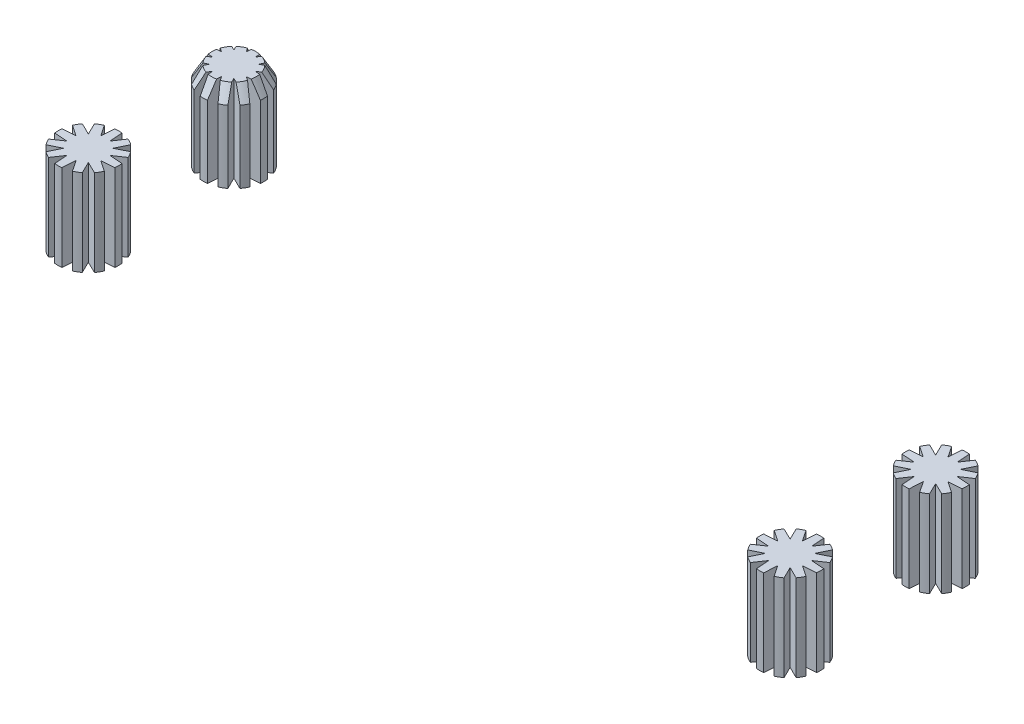
SolidWorks part; units mm, degrees
ref_plane "Front Plane" through (0, 0, 0) normal (0, 0, 1) x (1, 0, 0)
ref_plane "Top Plane" through (0, 0, 0) normal (0, 1, 0) x (1, 0, 0)
ref_plane "Right Plane" through (0, 0, 0) normal (1, 0, 0) x (0, 0, -1)
sketch "Sketch2" plane through (0, 0, 0) normal (0, 1, 0) x (1, 0, 0)
  line L0 (-22.25, 13.4082) -> (-22.25, -6080.7708) construction
  line L1 (-20.25, -10) -> (20.25, -10) construction
  line L2 (-20.25, -10) -> (-20.25, 10) construction
  line L3 (-20.25, 10) -> (20.25, 10) construction
  line L4 (20.25, -10) -> (20.25, 10) construction
  line L5 (-20.25, -10) -> (20.25, 10) construction
  line L6 (-20.25, 10) -> (20.25, -10) construction
  line L7 (0, 0) -> (-50000, 0) construction
  line L9 (0, 0) -> (0, 50000) construction
  point P0 (0, 0)
  dimension "D1" = 2
  dimension "D3" = 40.5
  dimension "D4" = 20
sketch "Sketch4" plane through (0, 0, 0) normal (0, 1, 0) x (1, 0, 0)
  line L0 (-24.35, 5.0484) -> (-24.35, 50005.0484) construction
  line L1 (-24.6, 7.1351) -> (-24.6798, 5.9941)
  line L2 (-24.1, 7.1351) -> (-24.0202, 5.9941)
  line L3 (-22.25, 200013.4082) -> (-22.25, -206080.7708) construction
  line L4 (200000, 0) -> (-250000, 0) construction
  line L5 (-23.091, 6.7307) -> (-23.5924, 5.7027)
  line L6 (-23.524, 6.9807) -> (-24.1636, 6.0325)
  line L7 (-22.4193, 5.876) -> (-23.3675, 5.2364)
  line L8 (-22.6693, 6.309) -> (-23.6973, 5.8076)
  line L9 (-22.2649, 4.8) -> (-23.4059, 4.7202)
  line L10 (-22.2649, 5.3) -> (-23.4059, 5.3798)
  line L11 (-22.6693, 3.791) -> (-23.6973, 4.2924)
  line L12 (-22.4193, 4.224) -> (-23.3675, 4.8636)
  line L13 (-23.524, 3.1193) -> (-24.1636, 4.0675)
  line L14 (-23.091, 3.3693) -> (-23.5924, 4.3973)
  line L15 (-24.6, 2.9649) -> (-24.6798, 4.1059)
  line L16 (-24.1, 2.9649) -> (-24.0202, 4.1059)
  line L17 (-25.609, 3.3693) -> (-25.1076, 4.3973)
  line L18 (-25.176, 3.1193) -> (-24.5364, 4.0675)
  line L19 (-26.2807, 4.224) -> (-25.3325, 4.8636)
  line L20 (-26.0307, 3.791) -> (-25.0027, 4.2924)
  line L21 (-26.4351, 5.3) -> (-25.2941, 5.3798)
  line L22 (-26.4351, 4.8) -> (-25.2941, 4.7202)
  line L23 (-26.0307, 6.309) -> (-25.0027, 5.8076)
  line L24 (-26.2807, 5.876) -> (-25.3325, 5.2364)
  line L25 (-25.176, 6.9807) -> (-24.5364, 6.0325)
  line L26 (-25.609, 6.7307) -> (-25.1076, 5.7027)
  line L27 (0, 0) -> (-50000, 0) construction
  line L28 (0, 0) -> (0, 50000) construction
  line L29 (-25.609, -6.7307) -> (-25.1076, -5.7027)
  line L30 (-25.176, -6.9807) -> (-24.5364, -6.0325)
  line L31 (-26.2807, -5.876) -> (-25.3325, -5.2364)
  line L32 (-26.0307, -6.309) -> (-25.0027, -5.8076)
  line L33 (-26.4351, -4.8) -> (-25.2941, -4.7202)
  line L34 (-26.4351, -5.3) -> (-25.2941, -5.3798)
  line L35 (-26.0307, -3.791) -> (-25.0027, -4.2924)
  line L36 (-26.2807, -4.224) -> (-25.3325, -4.8636)
  line L37 (-25.176, -3.1193) -> (-24.5364, -4.0675)
  line L38 (-25.609, -3.3693) -> (-25.1076, -4.3973)
  line L39 (-24.1, -2.9649) -> (-24.0202, -4.1059)
  line L40 (-24.6, -2.9649) -> (-24.6798, -4.1059)
  line L41 (-23.091, -3.3693) -> (-23.5924, -4.3973)
  line L42 (-23.524, -3.1193) -> (-24.1636, -4.0675)
  line L43 (-22.4193, -4.224) -> (-23.3675, -4.8636)
  line L44 (-22.6693, -3.791) -> (-23.6973, -4.2924)
  line L45 (-22.2649, -5.3) -> (-23.4059, -5.3798)
  line L46 (-22.2649, -4.8) -> (-23.4059, -4.7202)
  line L47 (-22.6693, -6.309) -> (-23.6973, -5.8076)
  line L48 (-22.4193, -5.876) -> (-23.3675, -5.2364)
  line L49 (-23.524, -6.9807) -> (-24.1636, -6.0325)
  line L50 (-23.091, -6.7307) -> (-23.5924, -5.7027)
  line L51 (-24.1, -7.1351) -> (-24.0202, -5.9941)
  line L52 (-24.6, -7.1351) -> (-24.6798, -5.9941)
  line L53 (24.6, -7.1351) -> (24.6798, -5.9941)
  line L54 (24.1, -7.1351) -> (24.0202, -5.9941)
  line L55 (23.091, -6.7307) -> (23.5924, -5.7027)
  line L56 (23.524, -6.9807) -> (24.1636, -6.0325)
  line L57 (22.4193, -5.876) -> (23.3675, -5.2364)
  line L58 (22.6693, -6.309) -> (23.6973, -5.8076)
  line L59 (22.2649, -4.8) -> (23.4059, -4.7202)
  line L60 (22.2649, -5.3) -> (23.4059, -5.3798)
  line L61 (22.6693, -3.791) -> (23.6973, -4.2924)
  line L62 (22.4193, -4.224) -> (23.3675, -4.8636)
  line L63 (23.524, -3.1193) -> (24.1636, -4.0675)
  line L64 (23.091, -3.3693) -> (23.5924, -4.3973)
  line L65 (24.6, -2.9649) -> (24.6798, -4.1059)
  line L66 (24.1, -2.9649) -> (24.0202, -4.1059)
  line L67 (25.609, -3.3693) -> (25.1076, -4.3973)
  line L68 (25.176, -3.1193) -> (24.5364, -4.0675)
  line L69 (26.2807, -4.224) -> (25.3325, -4.8636)
  line L70 (26.0307, -3.791) -> (25.0027, -4.2924)
  line L71 (26.4351, -5.3) -> (25.2941, -5.3798)
  line L72 (26.4351, -4.8) -> (25.2941, -4.7202)
  line L73 (26.0307, -6.309) -> (25.0027, -5.8076)
  line L74 (26.2807, -5.876) -> (25.3325, -5.2364)
  line L75 (25.176, -6.9807) -> (24.5364, -6.0325)
  line L76 (25.609, -6.7307) -> (25.1076, -5.7027)
  line L77 (25.609, 6.7307) -> (25.1076, 5.7027)
  line L78 (25.176, 6.9807) -> (24.5364, 6.0325)
  line L79 (26.2807, 5.876) -> (25.3325, 5.2364)
  line L80 (26.0307, 6.309) -> (25.0027, 5.8076)
  line L81 (26.4351, 4.8) -> (25.2941, 4.7202)
  line L82 (26.4351, 5.3) -> (25.2941, 5.3798)
  line L83 (26.0307, 3.791) -> (25.0027, 4.2924)
  line L84 (26.2807, 4.224) -> (25.3325, 4.8636)
  line L85 (25.176, 3.1193) -> (24.5364, 4.0675)
  line L86 (25.609, 3.3693) -> (25.1076, 4.3973)
  line L87 (24.1, 2.9649) -> (24.0202, 4.1059)
  line L88 (24.6, 2.9649) -> (24.6798, 4.1059)
  line L89 (23.091, 3.3693) -> (23.5924, 4.3973)
  line L90 (23.524, 3.1193) -> (24.1636, 4.0675)
  line L91 (22.4193, 4.224) -> (23.3675, 4.8636)
  line L92 (22.6693, 3.791) -> (23.6973, 4.2924)
  line L93 (22.2649, 5.3) -> (23.4059, 5.3798)
  line L94 (22.2649, 4.8) -> (23.4059, 4.7202)
  line L95 (22.6693, 6.309) -> (23.6973, 5.8076)
  line L96 (22.4193, 5.876) -> (23.3675, 5.2364)
  line L97 (23.524, 6.9807) -> (24.1636, 6.0325)
  line L98 (23.091, 6.7307) -> (23.5924, 5.7027)
  line L99 (24.1, 7.1351) -> (24.0202, 5.9941)
  line L100 (24.6, 7.1351) -> (24.6798, 5.9941)
  circle A0 centre (-24.35, 5.05) radius 1 construction
  circle A2 centre (-24.35, 5.05) radius 2.1 construction
  arc A3 (-24.1, 7.1351) -> (-24.6, 7.1351) centre (-24.35, 5.05) ccw
  arc A4 (-24.6798, 5.9941) -> (-24.0202, 5.9941) centre (-24.35, 5.05) cw
  arc A5 (-23.091, 6.7307) -> (-23.524, 6.9807) centre (-24.35, 5.05) ccw
  arc A6 (-24.1636, 6.0325) -> (-23.5924, 5.7027) centre (-24.35, 5.05) cw
  arc A7 (-22.4193, 5.876) -> (-22.6693, 6.309) centre (-24.35, 5.05) ccw
  arc A8 (-23.6973, 5.8076) -> (-23.3675, 5.2364) centre (-24.35, 5.05) cw
  arc A9 (-22.2649, 4.8) -> (-22.2649, 5.3) centre (-24.35, 5.05) ccw
  arc A10 (-23.4059, 5.3798) -> (-23.4059, 4.7202) centre (-24.35, 5.05) cw
  arc A11 (-22.6693, 3.791) -> (-22.4193, 4.224) centre (-24.35, 5.05) ccw
  arc A12 (-23.3675, 4.8636) -> (-23.6973, 4.2924) centre (-24.35, 5.05) cw
  arc A13 (-23.524, 3.1193) -> (-23.091, 3.3693) centre (-24.35, 5.05) ccw
  arc A14 (-23.5924, 4.3973) -> (-24.1636, 4.0675) centre (-24.35, 5.05) cw
  arc A15 (-24.6, 2.9649) -> (-24.1, 2.9649) centre (-24.35, 5.05) ccw
  arc A16 (-24.0202, 4.1059) -> (-24.6798, 4.1059) centre (-24.35, 5.05) cw
  arc A17 (-25.609, 3.3693) -> (-25.176, 3.1193) centre (-24.35, 5.05) ccw
  arc A18 (-24.5364, 4.0675) -> (-25.1076, 4.3973) centre (-24.35, 5.05) cw
  arc A19 (-26.2807, 4.224) -> (-26.0307, 3.791) centre (-24.35, 5.05) ccw
  arc A20 (-25.0027, 4.2924) -> (-25.3325, 4.8636) centre (-24.35, 5.05) cw
  arc A21 (-26.4351, 5.3) -> (-26.4351, 4.8) centre (-24.35, 5.05) ccw
  arc A22 (-25.2941, 4.7202) -> (-25.2941, 5.3798) centre (-24.35, 5.05) cw
  arc A23 (-26.0307, 6.309) -> (-26.2807, 5.876) centre (-24.35, 5.05) ccw
  arc A24 (-25.3325, 5.2364) -> (-25.0027, 5.8076) centre (-24.35, 5.05) cw
  arc A25 (-25.176, 6.9807) -> (-25.609, 6.7307) centre (-24.35, 5.05) ccw
  arc A26 (-25.1076, 5.7027) -> (-24.5364, 6.0325) centre (-24.35, 5.05) cw
  circle A27 centre (-24.35, -5.05) radius 2.1 construction
  circle A28 centre (-24.35, -5.05) radius 1 construction
  arc A29 (-25.1076, -5.7027) -> (-24.5364, -6.0325) centre (-24.35, -5.05) ccw
  arc A30 (-25.176, -6.9807) -> (-25.609, -6.7307) centre (-24.35, -5.05) cw
  arc A31 (-25.3325, -5.2364) -> (-25.0027, -5.8076) centre (-24.35, -5.05) ccw
  arc A32 (-26.0307, -6.309) -> (-26.2807, -5.876) centre (-24.35, -5.05) cw
  arc A33 (-25.2941, -4.7202) -> (-25.2941, -5.3798) centre (-24.35, -5.05) ccw
  arc A34 (-26.4351, -5.3) -> (-26.4351, -4.8) centre (-24.35, -5.05) cw
  arc A35 (-25.0027, -4.2924) -> (-25.3325, -4.8636) centre (-24.35, -5.05) ccw
  arc A36 (-26.2807, -4.224) -> (-26.0307, -3.791) centre (-24.35, -5.05) cw
  arc A37 (-24.5364, -4.0675) -> (-25.1076, -4.3973) centre (-24.35, -5.05) ccw
  arc A38 (-25.609, -3.3693) -> (-25.176, -3.1193) centre (-24.35, -5.05) cw
  arc A39 (-24.0202, -4.1059) -> (-24.6798, -4.1059) centre (-24.35, -5.05) ccw
  arc A40 (-24.6, -2.9649) -> (-24.1, -2.9649) centre (-24.35, -5.05) cw
  arc A41 (-23.5924, -4.3973) -> (-24.1636, -4.0675) centre (-24.35, -5.05) ccw
  arc A42 (-23.524, -3.1193) -> (-23.091, -3.3693) centre (-24.35, -5.05) cw
  arc A43 (-23.3675, -4.8636) -> (-23.6973, -4.2924) centre (-24.35, -5.05) ccw
  arc A44 (-22.6693, -3.791) -> (-22.4193, -4.224) centre (-24.35, -5.05) cw
  arc A45 (-23.4059, -5.3798) -> (-23.4059, -4.7202) centre (-24.35, -5.05) ccw
  arc A46 (-22.2649, -4.8) -> (-22.2649, -5.3) centre (-24.35, -5.05) cw
  arc A47 (-23.6973, -5.8076) -> (-23.3675, -5.2364) centre (-24.35, -5.05) ccw
  arc A48 (-22.4193, -5.876) -> (-22.6693, -6.309) centre (-24.35, -5.05) cw
  arc A49 (-24.1636, -6.0325) -> (-23.5924, -5.7027) centre (-24.35, -5.05) ccw
  arc A50 (-23.091, -6.7307) -> (-23.524, -6.9807) centre (-24.35, -5.05) cw
  arc A51 (-24.6798, -5.9941) -> (-24.0202, -5.9941) centre (-24.35, -5.05) ccw
  arc A52 (-24.1, -7.1351) -> (-24.6, -7.1351) centre (-24.35, -5.05) cw
  circle A53 centre (24.35, -5.05) radius 1 construction
  circle A54 centre (24.35, -5.05) radius 2.1 construction
  arc A55 (24.1, -7.1351) -> (24.6, -7.1351) centre (24.35, -5.05) ccw
  arc A56 (24.6798, -5.9941) -> (24.0202, -5.9941) centre (24.35, -5.05) cw
  arc A57 (23.091, -6.7307) -> (23.524, -6.9807) centre (24.35, -5.05) ccw
  arc A58 (24.1636, -6.0325) -> (23.5924, -5.7027) centre (24.35, -5.05) cw
  arc A59 (22.4193, -5.876) -> (22.6693, -6.309) centre (24.35, -5.05) ccw
  arc A60 (23.6973, -5.8076) -> (23.3675, -5.2364) centre (24.35, -5.05) cw
  arc A61 (22.2649, -4.8) -> (22.2649, -5.3) centre (24.35, -5.05) ccw
  arc A62 (23.4059, -5.3798) -> (23.4059, -4.7202) centre (24.35, -5.05) cw
  arc A63 (22.6693, -3.791) -> (22.4193, -4.224) centre (24.35, -5.05) ccw
  arc A64 (23.3675, -4.8636) -> (23.6973, -4.2924) centre (24.35, -5.05) cw
  arc A65 (23.524, -3.1193) -> (23.091, -3.3693) centre (24.35, -5.05) ccw
  arc A66 (23.5924, -4.3973) -> (24.1636, -4.0675) centre (24.35, -5.05) cw
  arc A67 (24.6, -2.9649) -> (24.1, -2.9649) centre (24.35, -5.05) ccw
  arc A68 (24.0202, -4.1059) -> (24.6798, -4.1059) centre (24.35, -5.05) cw
  arc A69 (25.609, -3.3693) -> (25.176, -3.1193) centre (24.35, -5.05) ccw
  arc A70 (24.5364, -4.0675) -> (25.1076, -4.3973) centre (24.35, -5.05) cw
  arc A71 (26.2807, -4.224) -> (26.0307, -3.791) centre (24.35, -5.05) ccw
  arc A72 (25.0027, -4.2924) -> (25.3325, -4.8636) centre (24.35, -5.05) cw
  arc A73 (26.4351, -5.3) -> (26.4351, -4.8) centre (24.35, -5.05) ccw
  arc A74 (25.2941, -4.7202) -> (25.2941, -5.3798) centre (24.35, -5.05) cw
  arc A75 (26.0307, -6.309) -> (26.2807, -5.876) centre (24.35, -5.05) ccw
  arc A76 (25.3325, -5.2364) -> (25.0027, -5.8076) centre (24.35, -5.05) cw
  arc A77 (25.176, -6.9807) -> (25.609, -6.7307) centre (24.35, -5.05) ccw
  arc A78 (25.1076, -5.7027) -> (24.5364, -6.0325) centre (24.35, -5.05) cw
  circle A79 centre (24.35, 5.05) radius 2.1 construction
  circle A80 centre (24.35, 5.05) radius 1 construction
  arc A81 (25.1076, 5.7027) -> (24.5364, 6.0325) centre (24.35, 5.05) ccw
  arc A82 (25.176, 6.9807) -> (25.609, 6.7307) centre (24.35, 5.05) cw
  arc A83 (25.3325, 5.2364) -> (25.0027, 5.8076) centre (24.35, 5.05) ccw
  arc A84 (26.0307, 6.309) -> (26.2807, 5.876) centre (24.35, 5.05) cw
  arc A85 (25.2941, 4.7202) -> (25.2941, 5.3798) centre (24.35, 5.05) ccw
  arc A86 (26.4351, 5.3) -> (26.4351, 4.8) centre (24.35, 5.05) cw
  arc A87 (25.0027, 4.2924) -> (25.3325, 4.8636) centre (24.35, 5.05) ccw
  arc A88 (26.2807, 4.224) -> (26.0307, 3.791) centre (24.35, 5.05) cw
  arc A89 (24.5364, 4.0675) -> (25.1076, 4.3973) centre (24.35, 5.05) ccw
  arc A90 (25.609, 3.3693) -> (25.176, 3.1193) centre (24.35, 5.05) cw
  arc A91 (24.0202, 4.1059) -> (24.6798, 4.1059) centre (24.35, 5.05) ccw
  arc A92 (24.6, 2.9649) -> (24.1, 2.9649) centre (24.35, 5.05) cw
  arc A93 (23.5924, 4.3973) -> (24.1636, 4.0675) centre (24.35, 5.05) ccw
  arc A94 (23.524, 3.1193) -> (23.091, 3.3693) centre (24.35, 5.05) cw
  arc A95 (23.3675, 4.8636) -> (23.6973, 4.2924) centre (24.35, 5.05) ccw
  arc A96 (22.6693, 3.791) -> (22.4193, 4.224) centre (24.35, 5.05) cw
  arc A97 (23.4059, 5.3798) -> (23.4059, 4.7202) centre (24.35, 5.05) ccw
  arc A98 (22.2649, 4.8) -> (22.2649, 5.3) centre (24.35, 5.05) cw
  arc A99 (23.6973, 5.8076) -> (23.3675, 5.2364) centre (24.35, 5.05) ccw
  arc A100 (22.4193, 5.876) -> (22.6693, 6.309) centre (24.35, 5.05) cw
  arc A101 (24.1636, 6.0325) -> (23.5924, 5.7027) centre (24.35, 5.05) ccw
  arc A102 (23.091, 6.7307) -> (23.524, 6.9807) centre (24.35, 5.05) cw
  arc A103 (24.6798, 5.9941) -> (24.0202, 5.9941) centre (24.35, 5.05) ccw
  arc A104 (24.1, 7.1351) -> (24.6, 7.1351) centre (24.35, 5.05) cw
  point P11 (-24.35, 2.95)
  point P61 (-24.35, 5.05)
  point P115 (-24.35, -2.95)
  point P167 (24.35, -2.95)
  point P219 (24.35, 2.95)
  dimension "D1" = 4.2
  dimension "D4" = 2
  dimension "D2" = 4
  dimension "D3" = 0.25
  dimension "D5" = 2.95
  dimension "D6" = 12
extrude "Boss-Extrude3" add sketch "Sketch4" along normal blind 6 contours A26 A24 A22 A20 A18 A16 A14 A12 A10 A8 A6 A4 | A29 A51 A49 A47 A45 A43 A41 A39 A37 A35 A33 A31 | A81 A103 A101 A99 A97 A95 A93 A91 A89 A87 A85 A83 | A78 A76 A74 A72 A70 A68 A66 A64 A62 A60 A58 A56
chamfer "Chamfer3" distance 1 angle 30 12 edges at (-24.35, 6, -2.95) (-25.4, 6, -3.2313) (-26.1687, 6, -4) (-26.45, 6, -5.05) (-26.1687, 6, -6.1) (-25.4, 6, -6.8687) (-24.35, 6, -7.15) (-23.3, 6, -6.8687) (-22.5313, 6, -6.1) (-22.25, 6, -5.05) (-22.5313, 6, -4) (-23.3, 6, -3.2313)
